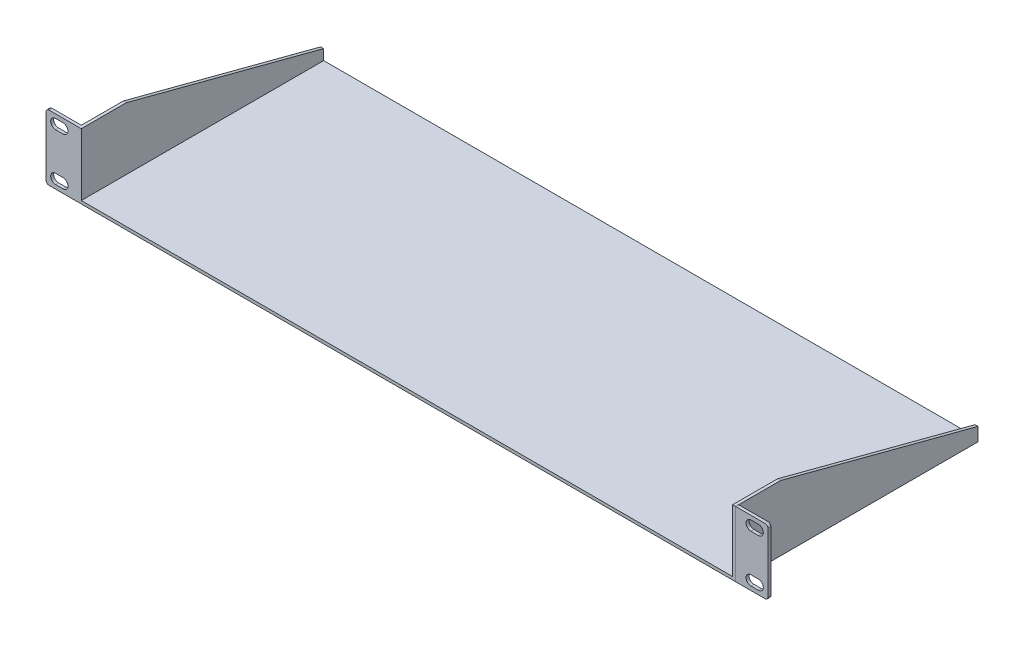
SolidWorks part; units mm, degrees
ref_plane "Front Plane" through (0, 0, 0) normal (0, 0, 1) x (1, 0, 0)
ref_plane "Top Plane" through (0, 0, 0) normal (0, 1, 0) x (1, 0, 0)
ref_plane "Right Plane" through (0, 0, 0) normal (1, 0, 0) x (0, 0, -1)
sketch "Sketch2" plane through (0, 0, 0) normal (0, 0, 1) x (1, 0, 0)
  line L12 (-19.7611, 37.5534) -> (-19.7611, -2.0466)
  line L13 (-17.7611, -4.0466) -> (1.8389, -4.0466)
  line L14 (1.8389, -4.0466) -> (1.8389, -2.4466)
  line L15 (1.8389, -2.4466) -> (1.8389, 37.9534)
  line L16 (1.8389, 37.9534) -> (1.8389, 39.5534)
  line L17 (1.8389, 39.5534) -> (-17.7611, 39.5534)
  line L24 (441.2389, -2.4466) -> (441.2389, -4.0466)
  line L25 (441.2389, -4.0466) -> (460.8389, -4.0466)
  line L26 (462.8389, -2.0466) -> (462.8389, 37.5534)
  line L27 (460.8389, 39.5534) -> (441.2389, 39.5534)
  line L28 (441.2389, 39.5534) -> (441.2389, 37.9534)
  line L29 (441.2389, 37.9534) -> (441.2389, -2.4466)
  arc A4 (-17.7611, 39.5534) -> (-19.7611, 37.5534) centre (-17.7611, 37.5534) ccw
  arc A5 (-19.7611, -2.0466) -> (-17.7611, -4.0466) centre (-17.7611, -2.0466) ccw
  arc A8 (460.8389, -4.0466) -> (462.8389, -2.0466) centre (460.8389, -2.0466) ccw
  arc A9 (462.8389, 37.5534) -> (460.8389, 39.5534) centre (460.8389, 37.5534) ccw
extrude "Boss-Extrude1" add sketch "Sketch2" along normal blind 2
sketch "Sketch3" plane through (0, 0, 0) normal (0, 0, 1) x (1, 0, 0)
  line L4 (-8.3611, -1.3766) -> (-13.3611, -1.3766)
  line L5 (-13.3611, 5.1234) -> (-8.3611, 5.1234)
  line L6 (-8.3611, 30.3734) -> (-13.3611, 30.3734)
  line L7 (-13.3611, 36.8734) -> (-8.3611, 36.8734)
  line L12 (456.4389, -1.3766) -> (451.4389, -1.3766)
  line L13 (451.4389, 5.1234) -> (456.4389, 5.1234)
  line L14 (456.4389, 30.3734) -> (451.4389, 30.3734)
  line L15 (451.4389, 36.8734) -> (456.4389, 36.8734)
  arc A4 (-8.3611, -1.3766) -> (-8.3611, 5.1234) centre (-8.3611, 1.8734) ccw
  arc A5 (-13.3611, 5.1234) -> (-13.3611, -1.3766) centre (-13.3611, 1.8734) ccw
  arc A6 (-8.3611, 30.3734) -> (-8.3611, 36.8734) centre (-8.3611, 33.6234) ccw
  arc A7 (-13.3611, 36.8734) -> (-13.3611, 30.3734) centre (-13.3611, 33.6234) ccw
  arc A12 (456.4389, -1.3766) -> (456.4389, 5.1234) centre (456.4389, 1.8734) ccw
  arc A13 (451.4389, 5.1234) -> (451.4389, -1.3766) centre (451.4389, 1.8734) ccw
  arc A14 (456.4389, 30.3734) -> (456.4389, 36.8734) centre (456.4389, 33.6234) ccw
  arc A15 (451.4389, 36.8734) -> (451.4389, 30.3734) centre (451.4389, 33.6234) ccw
extrude "Cut-Extrude4" cut sketch "Sketch3" against normal blind 2 and the other way through all
sketch "Sketch4" plane through (0, 0, 2) normal (0, 0, 1) x (1, 0, 0)
  line L0 (1.8389, 39.5534) -> (-17.7611, 39.5534) construction
  line L1 (1.8389, 39.5534) -> (3.8389, 39.5534)
  line L2 (1.8389, 39.5534) -> (1.8389, -4.0466)
  line L3 (1.8389, -4.0466) -> (441.2056, -4.0466)
  line L4 (441.2056, 39.5534) -> (441.2056, -4.0466)
  line L5 (1.8389, -4.0466) -> (1.8389, 39.5534) construction
  line L6 (3.8389, 39.5534) -> (3.8389, -2.0466)
  line L7 (3.8389, -2.0466) -> (439.2056, -2.0466)
  line L8 (439.2056, -2.0466) -> (439.2056, 39.5534)
  line L9 (439.2056, 39.5534) -> (441.2056, 39.5534)
  line L10 (439.2056, 39.5534) -> (441.2056, 39.5534)
  line L11 (3.8389, 39.5534) -> (1.8389, 39.5534)
  line M11 (1.8389, -4.0466) -> (1.8389, 39.5534)
  dimension "D1" = 2
  dimension "D2" = 2
  dimension "D3" = 2
extrude "Boss-Extrude2" add sketch "Sketch4" against normal blind 162 contours L9 L8 L7 L6 L1 L3 L4 M11
sketch "Sketch5" plane through (1.8389, 0, 0) normal (-1, 0, 0) x (0, 0, 1)
  line L0 (-160, -4.0466) -> (-160, 39.5534) construction
  line L1 (-160, 4.9075) -> (-28.0255, 39.5534)
  line L2 (-160, 39.5534) -> (0, 39.5534) construction
  line L3 (-28.0255, 39.5534) -> (-160, 39.5534)
  line L4 (-160, 39.5534) -> (-160, 4.9075)
extrude "Cut-Extrude5" cut sketch "Sketch5" against normal blind 517
